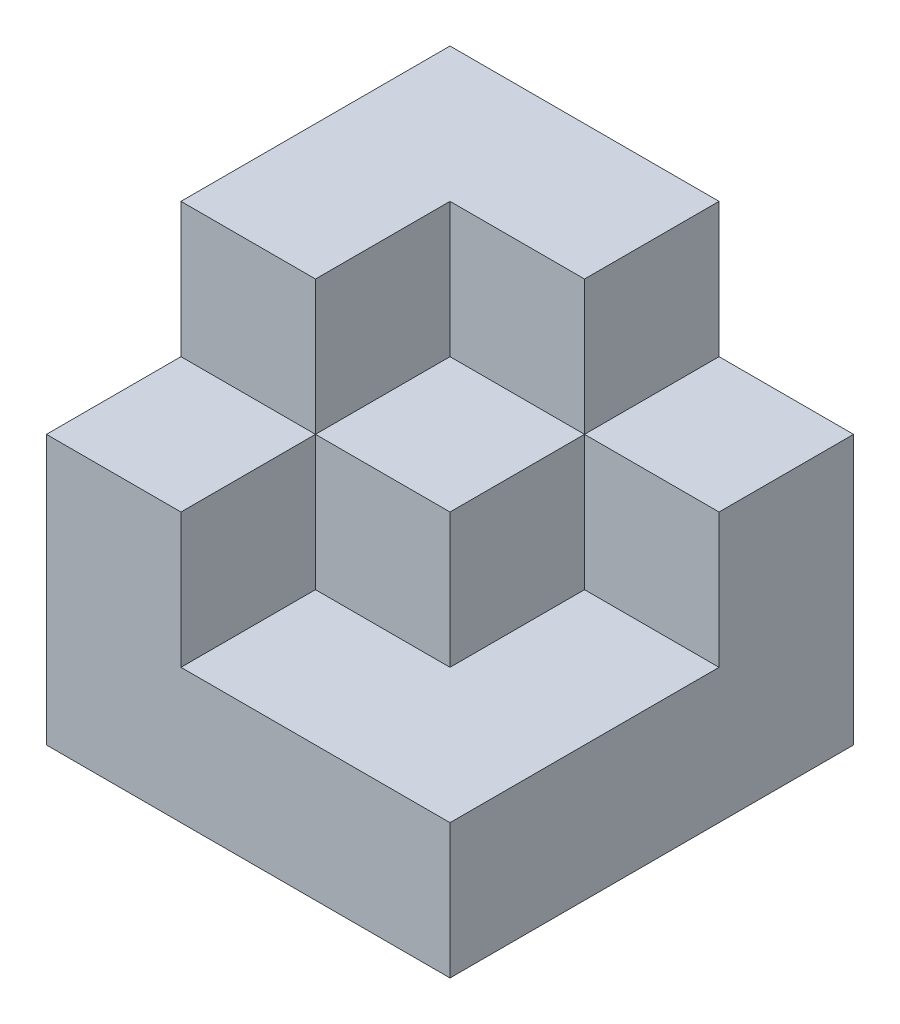
SolidWorks part; units mm, degrees
ref_plane "Alzado" through (0, 0, 0) normal (0, 0, 1) x (1, 0, 0)
ref_plane "Planta" through (0, 0, 0) normal (0, 1, 0) x (1, 0, 0)
ref_plane "Vista lateral" through (0, 0, 0) normal (1, 0, 0) x (0, 0, -1)
sketch "Croquis1" plane through (0, 0, 0) normal (0, 1, 0) x (1, 0, 0)
  line L1 (-30, 30) -> (30, 30)
  line L2 (-30, 30) -> (-30, -30)
  line L3 (-30, -30) -> (30, -30)
  line L4 (30, 30) -> (30, -30)
  line L5 (-30, 30) -> (30, -30) construction
  line L6 (-30, -30) -> (30, 30) construction
  point P0 (0, 0)
  dimension "D1" = 60
  dimension "D2" = 60
extrude "Saliente-Extruir1" add sketch "Croquis1" along normal blind 20
sketch "Croquis2" plane through (0, 20, 0) normal (0, 1, 0) x (1, 0, 0)
  line L1 (-30, -30) -> (-10, -30)
  line L2 (-30, -30) -> (-30, -10)
  line L3 (-30, -10) -> (-10, -10)
  line L4 (-10, -30) -> (-10, -10)
  dimension "D1" = 20
  dimension "D2" = 20
extrude "Saliente-Extruir2" add sketch "Croquis2" along normal blind 20
sketch "Croquis3" plane through (0, 20, 0) normal (0, 1, 0) x (1, 0, 0)
  line L0 (-30, 30) -> (-30, -10) construction
  line L1 (-30, 10) -> (-10, 10)
  line L2 (-30, 10) -> (-30, -10)
  line L3 (-30, -10) -> (-10, -10)
  line L4 (-10, 10) -> (-10, -10)
  dimension "D1" = 20
extrude "Saliente-Extruir4" add sketch "Croquis3" along normal blind 40
sketch "Croquis4" plane through (0, 20, 0) normal (0, 1, 0) x (1, 0, 0)
  line L0 (-30, 10) -> (-30, -10) construction
  line L1 (-30, 30) -> (10, 30)
  line L2 (-30, 30) -> (-30, 10)
  line L3 (-30, 10) -> (10, 10)
  line L4 (10, 30) -> (10, 10)
  dimension "D1" = 40
extrude "Saliente-Extruir5" add sketch "Croquis4" along normal blind 40
sketch "Croquis5" plane through (0, 20, 0) normal (0, 1, 0) x (1, 0, 0)
  line L0 (30, -30) -> (30, 30) construction
  line L1 (10, 30) -> (30, 30)
  line L2 (10, 30) -> (10, 10)
  line L3 (10, 10) -> (30, 10)
  line L4 (30, 30) -> (30, 10)
  dimension "D1" = 20
extrude "Saliente-Extruir6" add sketch "Croquis5" along normal blind 20
sketch "Croquis6" plane through (0, 20, 0) normal (0, 1, 0) x (1, 0, 0)
  line L1 (-10, 10) -> (10, 10)
  line L2 (-10, 10) -> (-10, -10)
  line L3 (-10, -10) -> (10, -10)
  line L4 (10, 10) -> (10, -10)
extrude "Saliente-Extruir7" add sketch "Croquis6" along normal blind 20
